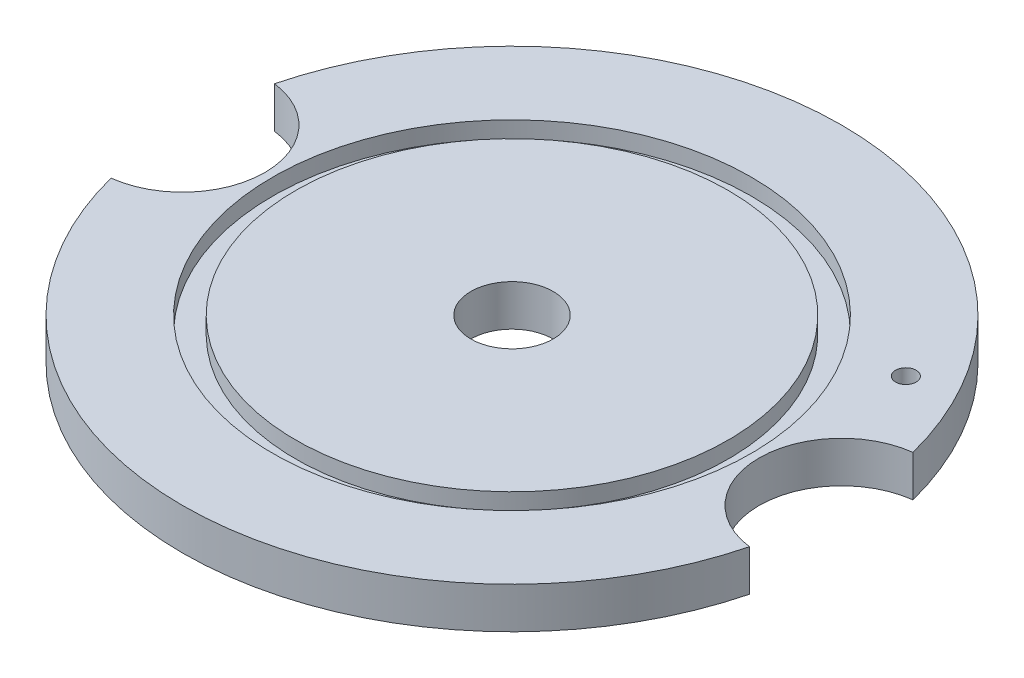
SolidWorks part; units mm, degrees
ref_plane "Front Plane" through (0, 0, 0) normal (0, 0, 1) x (1, 0, 0)
ref_plane "Top Plane" through (0, 0, 0) normal (0, 1, 0) x (1, 0, 0)
ref_plane "Right Plane" through (0, 0, 0) normal (1, 0, 0) x (0, 0, -1)
sketch "Sketch1" plane through (0, 0, 0) normal (0, 0, 1) x (1, 0, 0)
  line L0 (-33.3375, 6.35) -> (-33.3375, 3.81)
  line L1 (0, 0) -> (-50.8, 0)
  line L2 (0, 0) -> (0, 6.35)
  line L3 (0, 6.35) -> (-33.3375, 6.35)
  line L4 (-50.8, 0) -> (-50.8, 6.35)
  line L5 (-33.3375, 3.81) -> (-36.8935, 3.81)
  line L6 (-36.8935, 3.81) -> (-36.8935, 6.35)
  line L7 (-36.8935, 6.35) -> (-50.8, 6.35)
  dimension "D1" = 6.35
  dimension "D2" = 50.8
  dimension "D3" = 2.54
  dimension "D4" = 3.556
  dimension "D5" = 33.3375
revolve "Revolve1" add sketch "Sketch1" angle 360 about L2
hole_wizard "1/2 (0.5) Diameter Hole1" positions "Sketch2" profile "Sketch3" hole size "1/2" standard "ANSI Inch" end condition through all
sketch "Sketch2" plane through (0, 6.35, 0) normal (0, 1, 0) x (1, 0, 0)
  point P0 (0, 0)
sketch "Sketch3" plane through (0, 6.35, 0) normal (1, 0, 0) x (0, 0, 1)
  line L0 (0, 0) -> (0, 6.35)
  line L1 (0, 6.35) -> (6.35, 6.35)
  line L2 (6.35, 6.35) -> (6.35, 0)
  line L5 (6.35, 0) -> (0, 0)
  line L11 (0, -6.35) -> (0, 107.95) construction
  dimension "Thru Hole Dia." = 12.7
  dimension "Thru Hole Depth" = 6.35
hole_wizard "1 (1) Diameter Hole1" positions "Sketch4" profile "Sketch5" hole size "1" standard "ANSI Inch" end condition through all
sketch "Sketch4" plane through (0, 6.35, 0) normal (0, 1, 0) x (1, 0, 0)
  circle A0 centre (0, 0) radius 50.8 construction
  point P0 (50.8, 0)
  point P4 (-50.8, 0)
  point P8 (0, 0)
sketch "Sketch5" plane through (50.8, 6.35, 0) normal (1, 0, 0) x (0, 0, 1)
  line L0 (0, 0) -> (0, 6.35)
  line L1 (0, 6.35) -> (12.7, 6.35)
  line L2 (12.7, 6.35) -> (12.7, 0)
  line L5 (12.7, 0) -> (0, 0)
  line L11 (0, -6.35) -> (0, 107.95) construction
  dimension "Thru Hole Dia." = 25.4
  dimension "Thru Hole Depth" = 6.35
hole_wizard "1/8 (0.125) Diameter Hole1" positions "Sketch8" profile "Sketch7" hole size "1/8" standard "ANSI Inch" end condition through all
sketch "Sketch8" plane through (0, 6.35, 0) normal (0, 1, 0) x (1, 0, 0)
  line L0 (0, 0) -> (38.4948, 22.225) construction
  line L2 (0, 0) -> (46.6204, 0) construction
  point P0 (38.4948, 22.225)
  dimension "D1" = 30
  dimension "D2" = 44.45
sketch "Sketch7" plane through (38.4948, 6.35, -22.225) normal (1, 0, 0) x (0, 0, 1)
  line L0 (0, 0) -> (0, 6.35)
  line L1 (0, 6.35) -> (1.5875, 6.35)
  line L2 (1.5875, 6.35) -> (1.5875, 0)
  line L5 (1.5875, 0) -> (0, 0)
  line L11 (0, -6.35) -> (0, 107.95) construction
  dimension "Thru Hole Dia." = 3.175
  dimension "Thru Hole Depth" = 6.35
